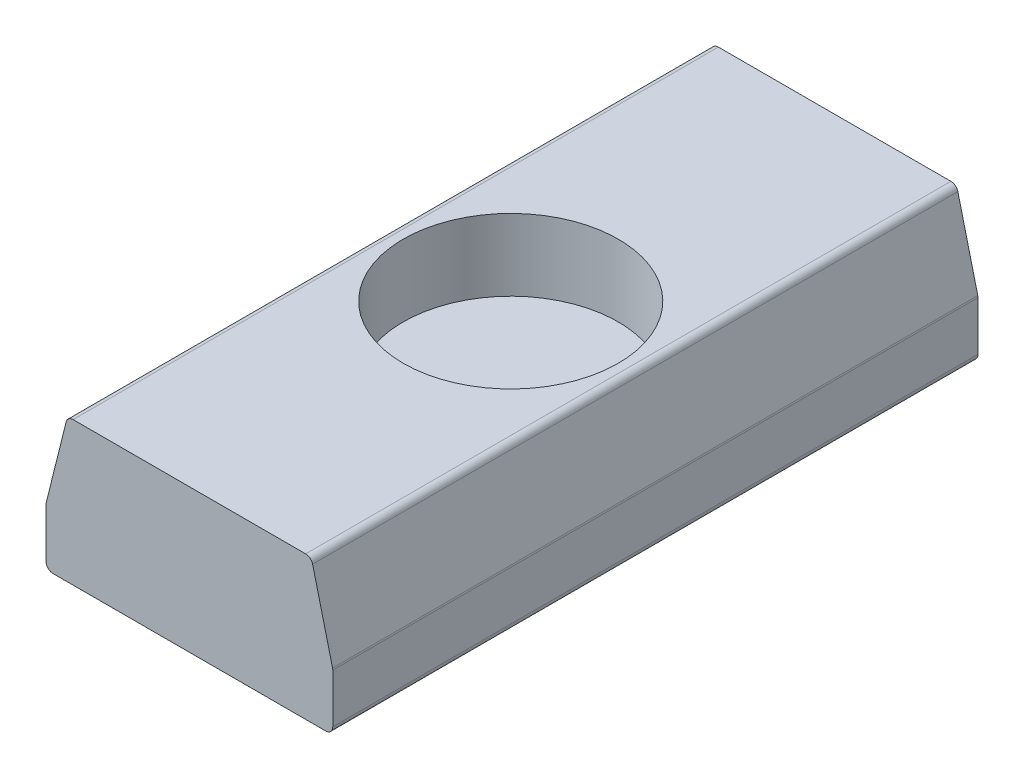
SolidWorks part; units mm, degrees
ref_plane "Front" through (0, 0, 0) normal (0, 0, 1) x (1, 0, 0)
ref_plane "Top" through (0, 0, 0) normal (0, 1, 0) x (1, 0, 0)
ref_plane "Right" through (0, 0, 0) normal (1, 0, 0) x (0, 0, -1)
sketch "Sketch1" plane through (0, 0, 0) normal (0, 0, 1) x (1, 0, 0)
  line L1 (-20, -10) -> (20, -10)
  line L2 (-20, -10) -> (-20, 10)
  line L3 (-20, 10) -> (20, 10)
  line L4 (20, -10) -> (20, 10)
  line L5 (-20, -10) -> (20, 10) construction
  line L6 (-20, 10) -> (20, -10) construction
  line L7 (17, 10) -> (20, -2.0323)
  line L8 (-17, 10) -> (-20, -2.0323)
  point P0 (0, 0)
  dimension "D1" = 40
  dimension "D2" = 20
  dimension "D3" = 3
  dimension "D4" = 3
extrude "Boss-Extrude1" add sketch "Sketch1" along normal blind 90 contours L3 L8 L2 L1 L4 L7
fillet "Fillet1" radius 1 6 edges at (-20, -10, 45) (20, -10, 45) (20, -2.0323, 45) (17, 10, 45) (-20, -2.0323, 45) (-17, 10, 45)
sketch "Sketch2" plane through (0, 10, 0) normal (0, 1, 0) x (1, 0, 0)
  circle A0 centre (0, -45.1784) radius 15
  dimension "D1" = 30
extrude "Cut-Extrude1" cut sketch "Sketch2" against normal blind 10
